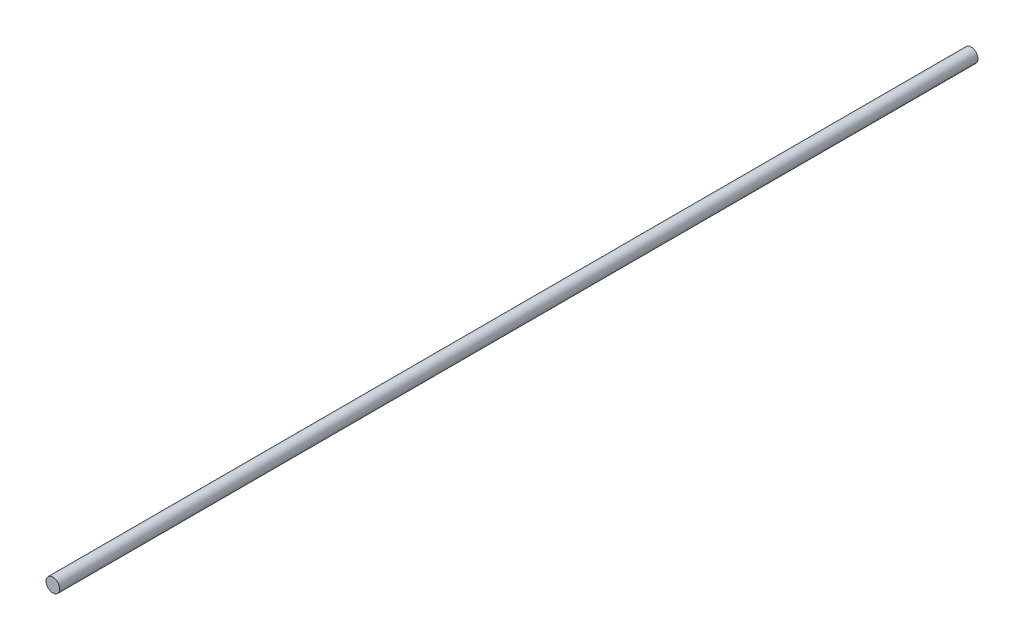
SolidWorks part; units mm, degrees
ref_plane "Front Plane" through (0, 0, 0) normal (0, 0, 1) x (1, 0, 0)
ref_plane "Top Plane" through (0, 0, 0) normal (0, 1, 0) x (1, 0, 0)
ref_plane "Right Plane" through (0, 0, 0) normal (1, 0, 0) x (0, 0, -1)
other "Configuration Table"
sketch "Sketch1" plane through (0, 0, 0) normal (0, 0, 1) x (1, 0, 0)
  circle A0 centre (350, 1060) radius 3
extrude "OVEN_yag_hatti_D6" add sketch "Sketch1" against normal blind 400 from offset 240 separate body
